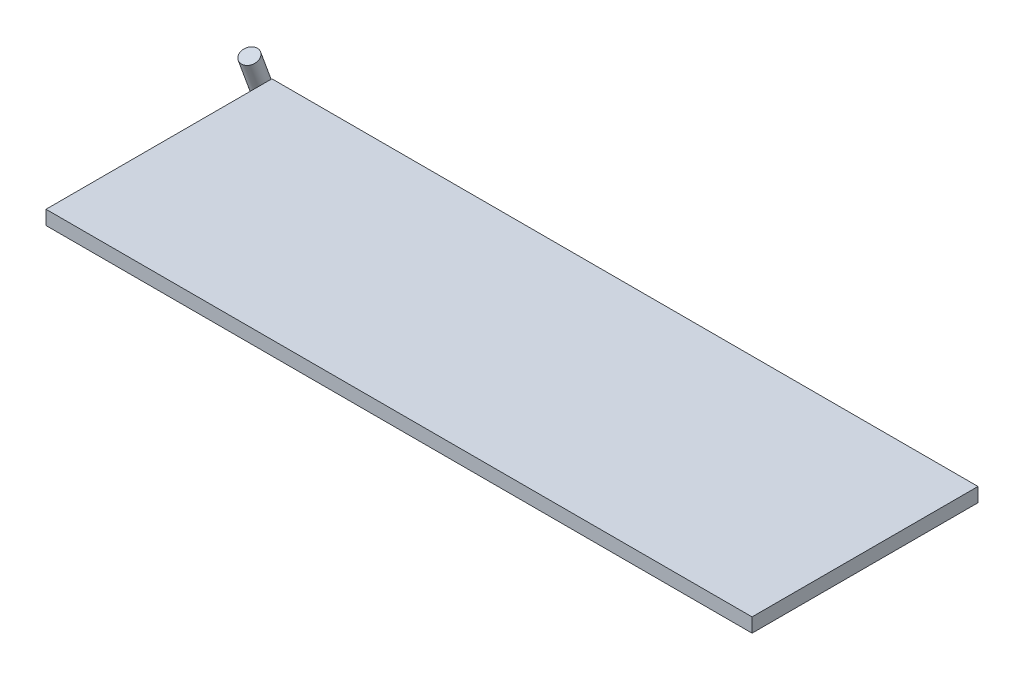
SolidWorks part; units mm, degrees
ref_plane "Front Plane" through (0, 0, 0) normal (0, 0, 1) x (1, 0, 0)
ref_plane "Top Plane" through (0, 0, 0) normal (0, 1, 0) x (1, 0, 0)
ref_plane "Right Plane" through (0, 0, 0) normal (1, 0, 0) x (0, 0, -1)
sketch "Sketch1" plane through (0, 0, 0) normal (0, 1, 0) x (1, 0, 0)
  line L1 (-225, 73.659) -> (25, 73.659)
  line L2 (-225, 73.659) -> (-225, -6.341)
  line L3 (-225, -6.341) -> (25, -6.341)
  line L4 (25, 73.659) -> (25, -6.341)
  dimension "D1" = 250
  dimension "D2" = 80
extrude "Boss-Extrude1" add sketch "Sketch1" along normal blind 5
ref_plane "Plane2" through (0, -23.6735, -8.6165) normal (0, -0.9397, -0.342) x (-1, 0, 0)
sketch "Sketch4" plane through (0, -23.6735, -8.6165) normal (0, -0.9397, -0.342) x (-1, 0, 0)
  circle A0 centre (228.6797, 69.3687) radius 3
  point P2 (219.0025, 61.7008)
  point P3 (213.0786, 64.8964)
  point P4 (234.9406, 67.4899)
  point P5 (228.6797, 69.3687)
extrude "Boss-Extrude3" add sketch "Sketch4" against normal blind 13 separate body
